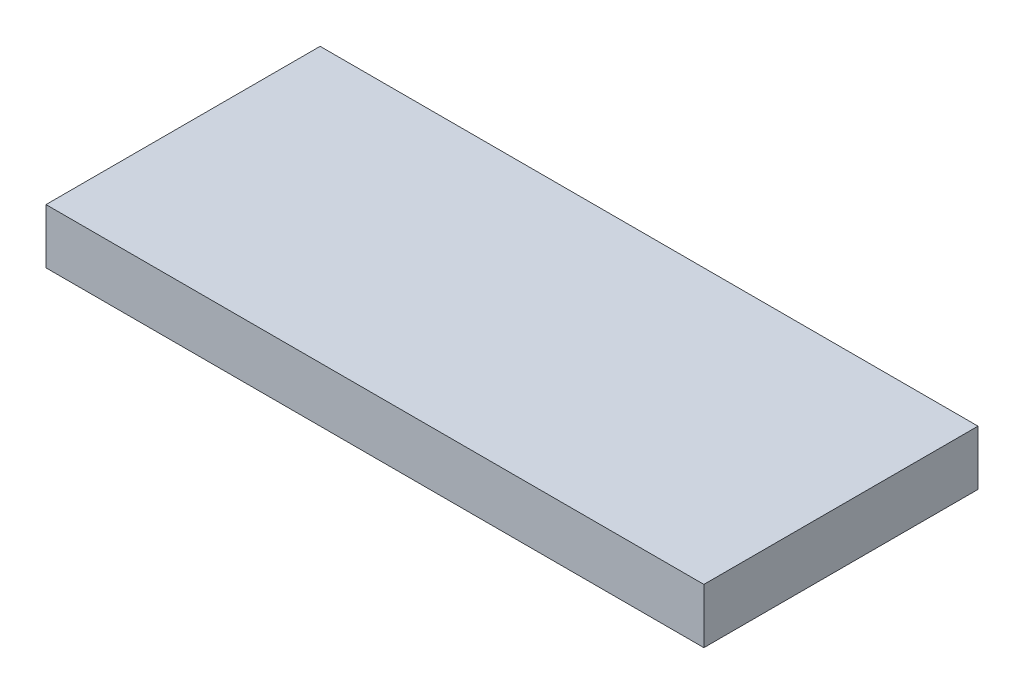
SolidWorks part; units mm, degrees
ref_plane "Alzado" through (0, 0, 0) normal (0, 0, 1) x (1, 0, 0)
ref_plane "Planta" through (0, 0, 0) normal (0, 1, 0) x (1, 0, 0)
ref_plane "Vista lateral" through (0, 0, 0) normal (1, 0, 0) x (0, 0, -1)
sketch "Sketch1" plane through (0, 0, 0) normal (0, 1, 0) x (1, 0, 0)
  line L1 (-60, 25) -> (60, 25)
  line L2 (-60, 25) -> (-60, -25)
  line L3 (-60, -25) -> (60, -25)
  line L4 (60, 25) -> (60, -25)
  line L5 (-60, 25) -> (60, -25) construction
  line L6 (-60, -25) -> (60, 25) construction
  point P0 (0, 0)
  dimension "D1" = 50
  dimension "D2" = 120
extrude "Boss-Extrude1" add sketch "Sketch1" along normal blind 10
